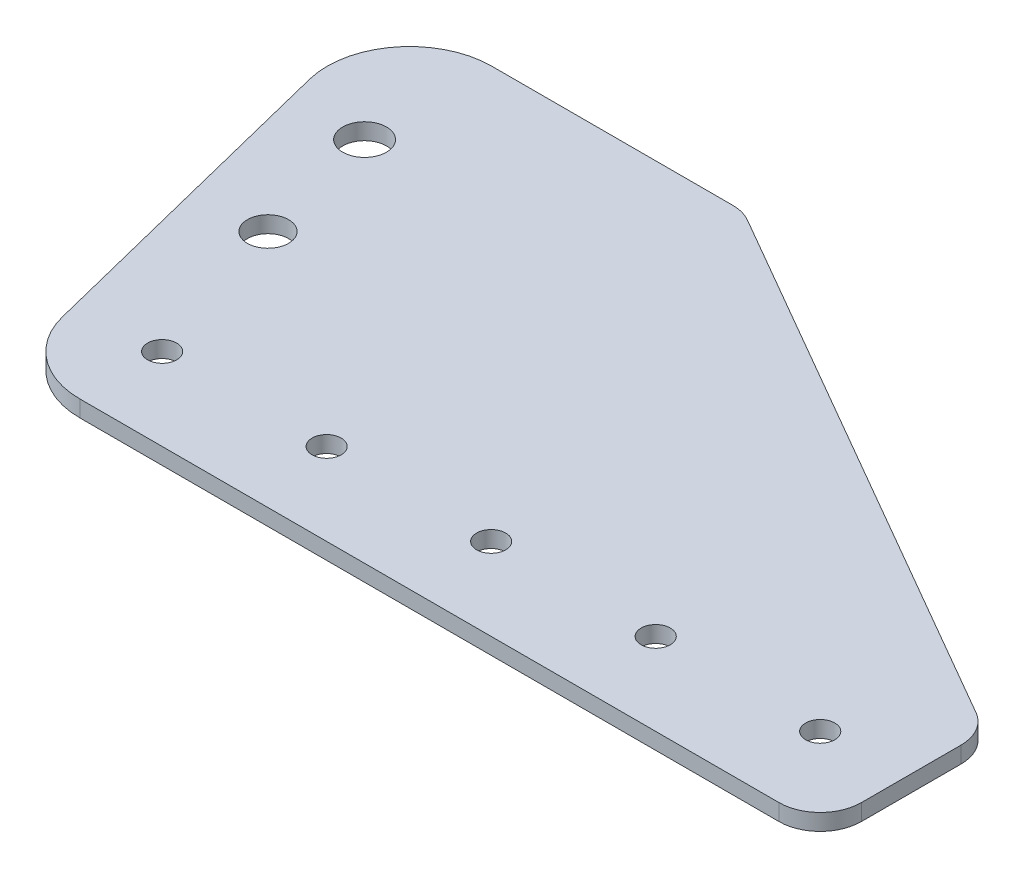
SolidWorks part; units mm, degrees
ref_plane "Front" through (0, 0, 0) normal (0, 0, 1) x (1, 0, 0)
ref_plane "Top" through (0, 0, 0) normal (0, 1, 0) x (1, 0, 0)
ref_plane "Right" through (0, 0, 0) normal (1, 0, 0) x (0, 0, -1)
sketch "Sketch1" plane through (0, 0, 0) normal (0, 1, 0) x (1, 0, 0)
  line L1 (127, -12.7) -> (12.7, -12.7)
  line L2 (127, -12.7) -> (127, 12.7)
  line L4 (0, -6.7235) -> (0, 17.1145) construction
  line L5 (0, -12.7) -> (749.3, -12.7) construction
  line L6 (-336.677, 63.5892) -> (-749.3, 63.5892) construction
  line L7 (0, 63.5892) -> (38.8574, 63.5892)
  line L9 (38.8574, 63.5892) -> (127, 12.7)
  line L11 (-12.3221, 47.814) -> (0.3779, -3.0751)
  arc A1 (12.7, -12.7) -> (0.3779, -3.0751) centre (12.7, 0) cw
  arc A2 (0, 63.5892) -> (-12.3221, 47.814) centre (0, 50.8892) ccw
  dimension "D2" = 25.4
  dimension "D9" = 12.7
  dimension "D3" = 30
  dimension "D1" = 127
  dimension "D4" = 25.4
extrude "Boss-Extrude1" add sketch "Sketch1" along normal blind 2.54
hole_wizard "1/4 Clearance Hole1" positions "Sketch2" profile "Sketch3" hole size "1/4" standard "ANSI Inch" end condition through all
sketch "Sketch2" plane through (0, 2.54, 0) normal (0, 1, 0) x (1, 0, 0)
  point P0 (0, 43.9568)
sketch "Sketch3" plane through (0, 2.54, -43.9568) normal (1, 0, 0) x (0, 0, 1)
  line L0 (0, 0) -> (0, 2.54)
  line L1 (0, 2.54) -> (3.3782, 2.54)
  line L2 (3.3782, 2.54) -> (3.3782, 0)
  line L5 (3.3782, 0) -> (0, 0)
  line L11 (0, -6.35) -> (0, 107.95) construction
  dimension "Thru Hole Dia." = 6.7564
  dimension "Thru Hole Depth" = 2.54
sketch "Sketch7" plane through (0, 2.54, 0) normal (0, 1, 0) x (1, 0, 0)
  line L0 (-12.3221, 47.814) -> (0.3779, -3.0751) construction
  line L1 (12.7, -12.7) -> (127, -12.7) construction
  point P0 (12.7, 0)
  point P5 (38.1, 0)
  point P6 (63.5, 0)
  point P7 (88.9, 0)
  point P8 (114.3, 0)
  point P16 (241.3, 0)
  point P17 (215.9, 0)
  point P18 (190.5, 0)
  point P19 (165.1, 0)
  point P20 (139.7, 0)
  dimension "D1" = 12.7
  dimension "D3" = 12.7
  dimension "D4" = 25.4
  dimension "D2" = 10
hole_wizard "#8 Clearance Hole3" positions "Sketch12" profile "Sketch13" hole size "#8" standard "ANSI Inch" end condition through all
sketch "Sketch12" plane through (0, 2.54, 0) normal (0, 1, 0) x (1, 0, 0)
  point P0 (12.7, 0)
  point P3 (38.1, 0)
  point P6 (63.5, 0)
  point P9 (88.9, 0)
  point P12 (114.3, 0)
sketch "Sketch13" plane through (12.7, 2.54, 0) normal (1, 0, 0) x (0, 0, 1)
  line L0 (0, 0) -> (0, 2.54)
  line L1 (0, 2.54) -> (2.2479, 2.54)
  line L2 (2.2479, 2.54) -> (2.2479, 0)
  line L5 (2.2479, 0) -> (0, 0)
  line L11 (0, -6.35) -> (0, 107.95) construction
  dimension "Thru Hole Dia." = 4.4958
  dimension "Thru Hole Depth" = 2.54
fillet "Fillet1" radius 6.35 3 edges at (127, 1.27, 12.7) (127, 1.27, -12.7) (38.8574, 1.27, -63.5892)
sketch "Sketch14" plane through (0, 2.54, 0) normal (0, 1, 0) x (1, 0, 0)
  line L0 (-5.3488, 32.4381) -> (17.6887, 21.7406) construction
  line L1 (23.0374, 33.2593) -> (-726.1288, 381.1369) construction
  line L2 (0, 43.9568) -> (-5.3488, 32.4381) construction
  line L3 (23.0374, 33.2593) -> (17.6887, 21.7406) construction
  circle A0 centre (4.8328, 24.2097) radius 3.175
  point P13 (6.17, 27.0894)
  dimension "D1" = 6.35
  dimension "D2" = 12.7
extrude "Cut-Extrude1" cut sketch "Sketch14" against normal blind 2.54
